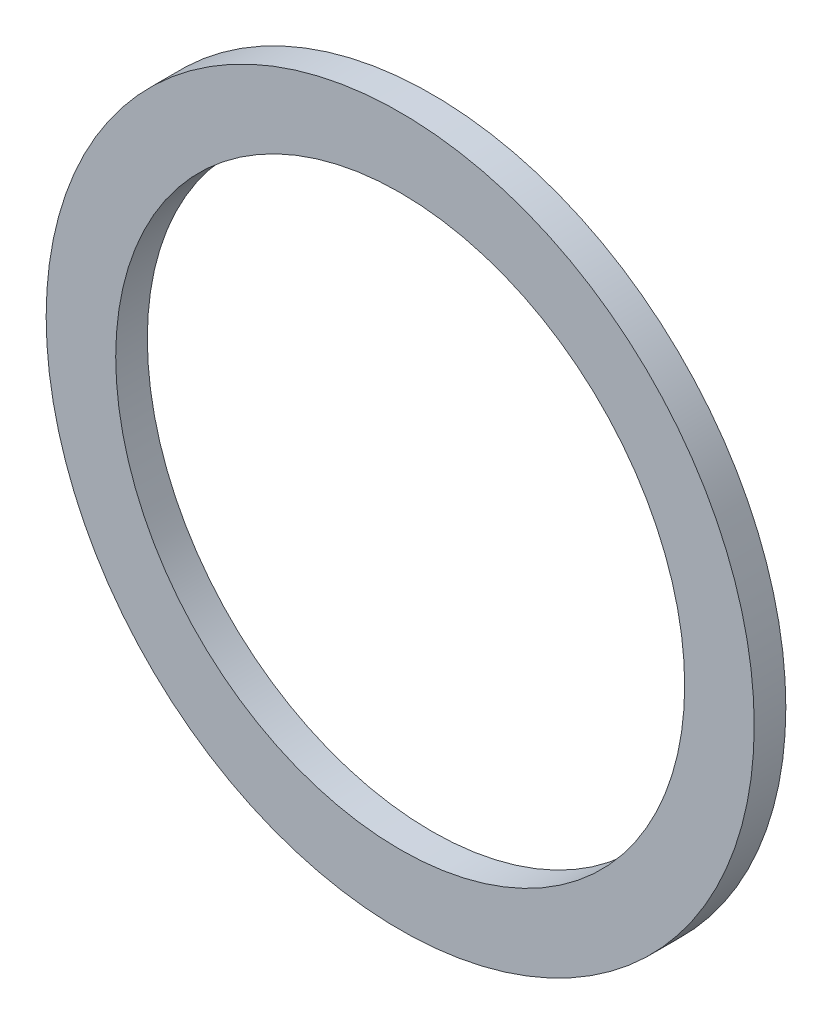
SolidWorks part; units mm, degrees
ref_plane "Alzado" through (0, 0, 0) normal (0, 0, 1) x (1, 0, 0)
ref_plane "Planta" through (0, 0, 0) normal (0, 1, 0) x (1, 0, 0)
ref_plane "Vista lateral" through (0, 0, 0) normal (1, 0, 0) x (0, 0, -1)
sketch "Croquis1" plane through (0, 0, 0) normal (0, 0, 1) x (1, 0, 0)
  circle A0 centre (0, 0) radius 11.2
  circle A1 centre (0, 0) radius 9
  dimension "D1" = 22.4
  dimension "D2" = 18
extrude "Saliente-Extruir1" add sketch "Croquis1" along normal blind 1
